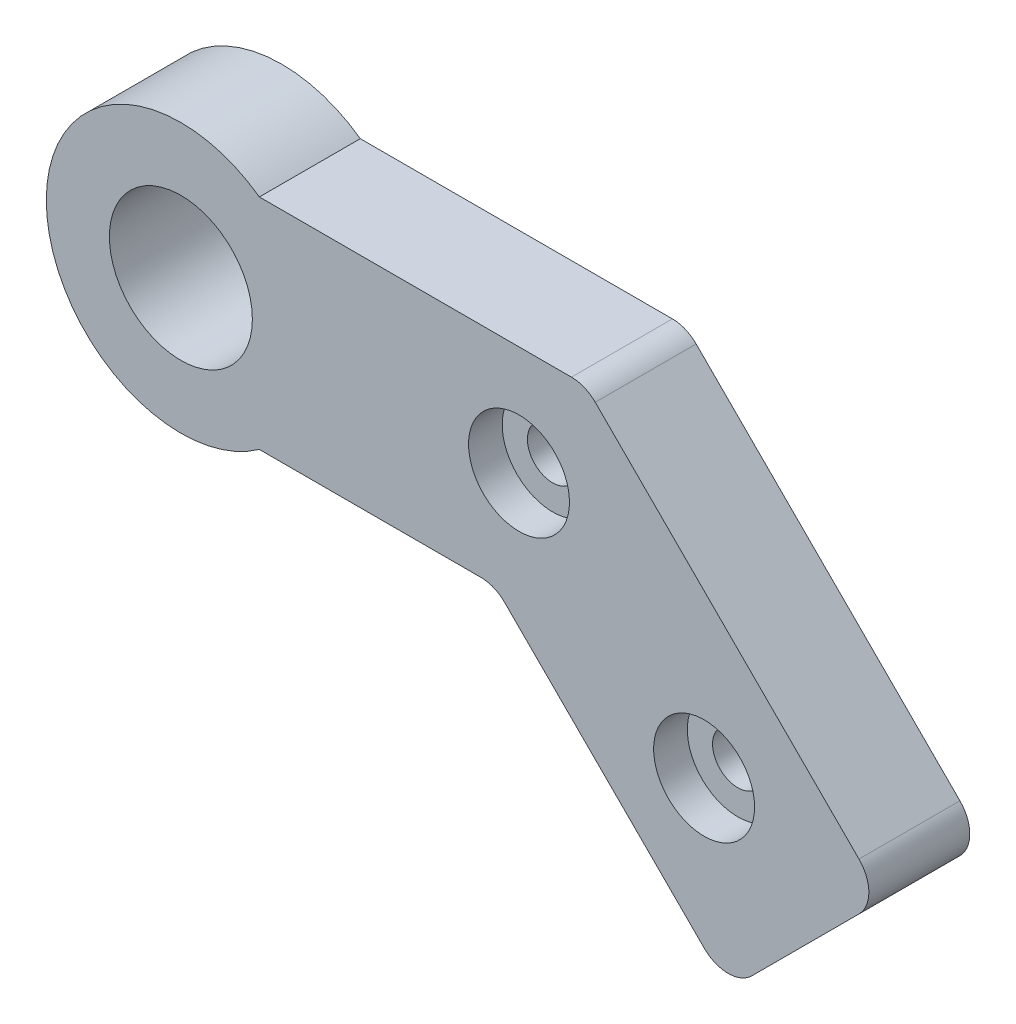
SolidWorks part; units mm, degrees
ref_plane "Plan de face" through (0, 0, 0) normal (0, 0, 1) x (1, 0, 0)
ref_plane "Plan de dessus" through (0, 0, 0) normal (0, 1, 0) x (1, 0, 0)
ref_plane "Plan de droite" through (0, 0, 0) normal (1, 0, 0) x (0, 0, -1)
sketch "Esquisse1" plane through (0, 0, 0) normal (0, 0, 1) x (1, 0, 0)
  line L0 (7.178, 7.5209) -> (4.2076, 4.5505) construction
  line L1 (-12.202, 7.5209) -> (7.178, 7.5209)
  line L3 (-12.2067, -5.4791) -> (1.7933, -5.4791)
  line L4 (-22.7913, 1.0226) -> (26.0996, 1.0226) construction
  line L7 (7.178, 7.5209) -> (24.8557, -10.1568)
  line L8 (1.7933, -5.4791) -> (15.6633, -19.3491)
  line L9 (24.8557, -10.1568) -> (15.6633, -19.3491)
  arc A0 (-12.202, 7.5209) -> (-12.2067, -5.4791) centre (-16.868, 1.0226) ccw
  point P0 (0, 0)
  dimension "D6" = 8
  dimension "D1" = 13
  dimension "D2" = 45
  dimension "D3" = 14
  dimension "D4" = 19.38
  dimension "D5" = 13
  dimension "D7" = 25
extrude "Boss.-Extru.1" add sketch "Esquisse1" along normal blind 6
fillet "Congé1" radius 2 4 edges at (24.8557, -10.1568, 3) (15.6633, -19.3491, 3) (1.7933, -5.4791, 3) (7.178, 7.5209, 3)
sketch "Esquisse2" plane through (0, 0, 6) normal (0, 0, 1) x (1, 0, 0)
  line L0 (3.232, 1.0209) -> (20.2595, -14.753) construction
  line L1 (6.3496, 7.5209) -> (-12.202, 7.5209) construction
  line L2 (-41.6901, 1.0209) -> (8.3116, 1.0209) construction
  line L3 (-12.5498, 7.7571) -> (-21.1863, -5.7118) construction
  line L5 (17.0775, -17.9349) -> (23.4415, -11.571) construction
  circle A0 centre (-16.868, 1.0226) radius 4.25
  circle A1 centre (3.232, 1.0209) radius 1.5
  circle A2 centre (14.2359, -9.1729) radius 1.5
  arc A4 (-12.202, 7.5209) -> (-12.2067, -5.4791) centre (-16.868, 1.0226) ccw construction
  dimension "D1" = 8.5
  dimension "D2" = 3
  dimension "D4" = 3
  dimension "D3" = 6.5
  dimension "D5" = 20.1
  dimension "D6" = 15
  dimension "D7" = 50.0017
extrude "Enlèv. mat.-Extru.1" cut sketch "Esquisse2" against normal through all
sketch "Esquisse3" plane through (0, 0, 6) normal (0, 0, 1) x (1, 0, 0)
  circle A0 centre (3.232, 1.0209) radius 3
  circle A1 centre (14.2359, -9.1729) radius 3
  dimension "D1" = 6
  dimension "D2" = 6
extrude "Enlèv. mat.-Extru.2" cut sketch "Esquisse3" against normal blind 2
